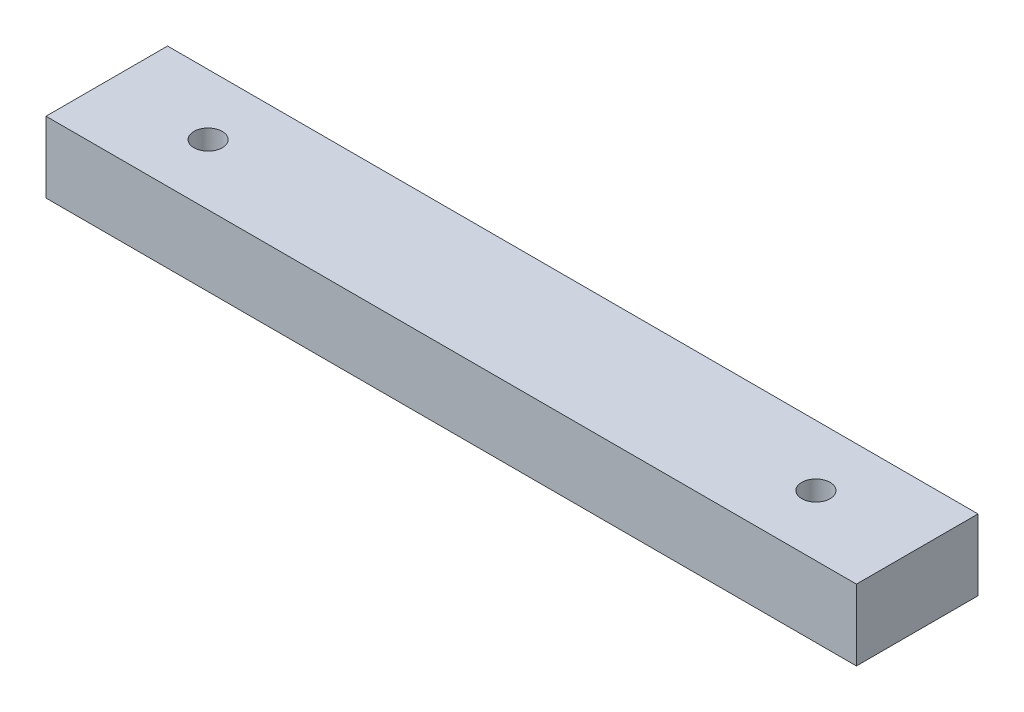
SolidWorks part; units mm, degrees
material "6061-T6 (SS)"
ref_plane "Front Plane" through (0, 0, 0) normal (0, 0, 1) x (1, 0, 0)
ref_plane "Top Plane" through (0, 0, 0) normal (0, 1, 0) x (1, 0, 0)
ref_plane "Right Plane" through (0, 0, 0) normal (1, 0, 0) x (0, 0, -1)
sketch "Sketch1" plane through (0, 0, 0) normal (0, 1, 0) x (1, 0, 0)
  line L1 (-200, -30) -> (200, -30)
  line L2 (-200, -30) -> (-200, 30)
  line L3 (-200, 30) -> (200, 30)
  line L4 (200, -30) -> (200, 30)
  line L5 (-200, -30) -> (200, 30) construction
  line L6 (-200, 30) -> (200, -30) construction
  point P0 (0, 0)
  dimension "D1" = 400
  dimension "D2" = 60
extrude "Boss-Extrude1" add sketch "Sketch1" along normal blind 35
sketch "Sketch2" plane through (0, 35, 0) normal (0, 1, 0) x (1, 0, 0)
  line L0 (200, -30) -> (200, 30) construction
  line L1 (200, 30) -> (-200, 30) construction
  line L2 (-200, 30) -> (-200, -30) construction
  circle A0 centre (-150, 0) radius 7
  circle A1 centre (150, 0) radius 7
  dimension "D1" = 14
  dimension "D2" = 14
  dimension "D3" = 50
  dimension "D4" = 30
  dimension "D5" = 50
  dimension "D6" = 30
extrude "Cut-Extrude1" cut sketch "Sketch2" against normal through all
hole_wizard "1/4-20 Tapped Hole1" positions "Sketch5" profile "Sketch6" tap size "1/4-20" standard "ANSI Inch"
sketch "Sketch5" plane through (0, 0, 0) normal (0, -1, 0) x (1, 0, 0)
  line L0 (-200, -30) -> (-200, 30) construction
  line L1 (-200, 30) -> (200, 30) construction
  line L2 (200, 30) -> (200, -30) construction
  point P2 (-168.77, 18.77)
  point P10 (-131.23, 18.77)
  point P12 (-131.23, -18.77)
  point P14 (-168.77, -18.77)
  point P19 (131.23, 18.77)
  point P21 (168.77, 18.77)
  point P23 (168.77, -18.77)
  point P25 (131.23, -18.77)
  dimension "D1" = 31.23
  dimension "D2" = 11.23
  dimension "D3" = 68.77
  dimension "D4" = 11.23
  dimension "D5" = 31.23
  dimension "D6" = 48.77
  dimension "D7" = 68.77
  dimension "D8" = 48.77
  dimension "D9" = 68.77
  dimension "D10" = 11.23
  dimension "D11" = 31.23
  dimension "D12" = 11.23
  dimension "D13" = 68.77
  dimension "D14" = 48.77
  dimension "D15" = 31.23
  dimension "D16" = 48.77
sketch "Sketch6" plane through (-168.77, 0, 18.77) normal (1, 0, 0) x (0, 0, -1)
  line L0 (0, 0) -> (0, 19.5338)
  line L1 (0, 19.5338) -> (2.5527, 18)
  line L2 (2.5527, 18) -> (2.5527, 1.2573)
  line L3 (2.5527, 1.2573) -> (3.81, 0)
  line L5 (3.81, 0) -> (0, 0)
  line L6 (-2.5527, 1.2573) -> (-3.81, 0) construction
  line L10 (0, 19.5338) -> (-2.5527, 18) construction
  line L11 (0, -6.35) -> (0, 107.95) construction
  dimension "Tap Drill Dia." = 5.1054
  dimension "Tap Drill Depth" = 18
  dimension "Near C'Sink Dia." = 7.62
  dimension "Near C'Sink Angle" = 90
  dimension "Drill Angle" = 118
cosmetic thread "Hole Thread1" parameters "D1"=12.7, "D2"=6.35
cosmetic thread "Hole Thread2" parameters "D1"=12.7, "D2"=6.35
cosmetic thread "Hole Thread3" parameters "D1"=12.7, "D2"=6.35
cosmetic thread "Hole Thread4" parameters "D1"=12.7, "D2"=6.35
cosmetic thread "Hole Thread5" parameters "D1"=12.7, "D2"=6.35
cosmetic thread "Hole Thread6" parameters "D1"=12.7, "D2"=6.35
cosmetic thread "Hole Thread7" parameters "D1"=12.7, "D2"=6.35
cosmetic thread "Hole Thread8" parameters "D1"=12.7, "D2"=6.35
equation "\"Crosshead Length\"= 400mm"
equation "\"Crosshead Width\"= 60mm"
equation "\"Height\"= 35mm"
equation "\"Screw Spacing\"= 300mm"
